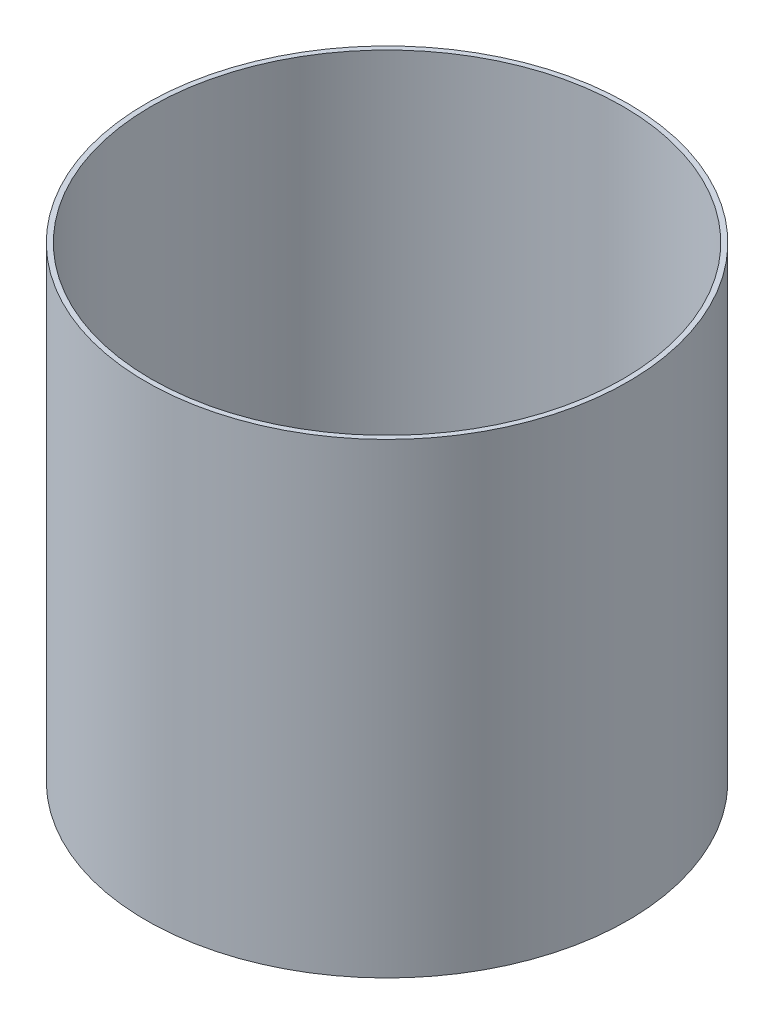
SolidWorks part; units mm, degrees
ref_plane "Front Plane" through (0, 0, 0) normal (0, 0, 1) x (1, 0, 0)
ref_plane "Top Plane" through (0, 0, 0) normal (0, 1, 0) x (1, 0, 0)
ref_plane "Right Plane" through (0, 0, 0) normal (1, 0, 0) x (0, 0, -1)
sketch "Sketch1" plane through (0, 0, 0) normal (0, 0, 1) x (1, 0, 0)
  line L0 (0, 0) -> (0, 1500) construction
  line L1 (0, 0) -> (775, 0) construction
  line L2 (775, 0) -> (775, 1500)
  line L3 (775, 1500) -> (759, 1500)
  line L4 (759, 1500) -> (759, 0)
  line L5 (759, 0) -> (775, 0)
  dimension "D1" = 1500
  dimension "D2" = 775
  dimension "D3" = 16
  dimension "D4" = 1500
revolve "Revolve1" add sketch "Sketch1" angle 360 about L0
